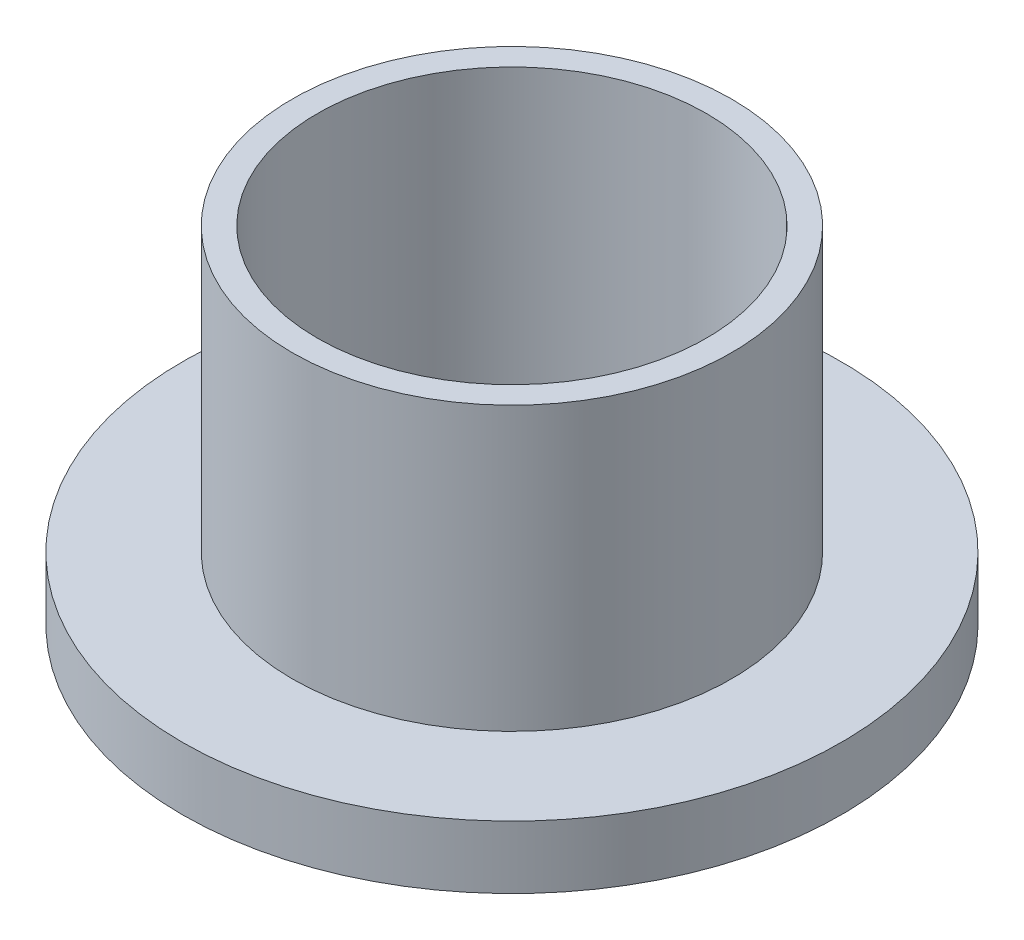
SolidWorks part; units mm, degrees
ref_plane "Front Plane" through (0, 0, 0) normal (0, 0, 1) x (1, 0, 0)
ref_plane "Top Plane" through (0, 0, 0) normal (0, 1, 0) x (1, 0, 0)
ref_plane "Right Plane" through (0, 0, 0) normal (1, 0, 0) x (0, 0, -1)
sketch "Sketch1" plane through (0, 0, 0) normal (0, 1, 0) x (1, 0, 0)
  circle A0 centre (0, 0) radius 5.25
  dimension "D1" = 10.5
extrude "Boss-Extrude1" add sketch "Sketch1" along normal blind 1
sketch "Sketch2" plane through (0, 1, 0) normal (0, 1, 0) x (1, 0, 0)
  circle A0 centre (0, 0) radius 2.5
  dimension "D1" = 5
extrude "Cut-Extrude1" cut sketch "Sketch2" against normal blind 1
sketch "Sketch3" plane through (0, 1, 0) normal (0, 1, 0) x (1, 0, 0)
  circle A0 centre (0, 0) radius 3.5
  circle A1 centre (0, 0) radius 3.1
  dimension "D1" = 0.4
  dimension "D2" = 7
extrude "Boss-Extrude2" add sketch "Sketch3" along normal blind 4.5
